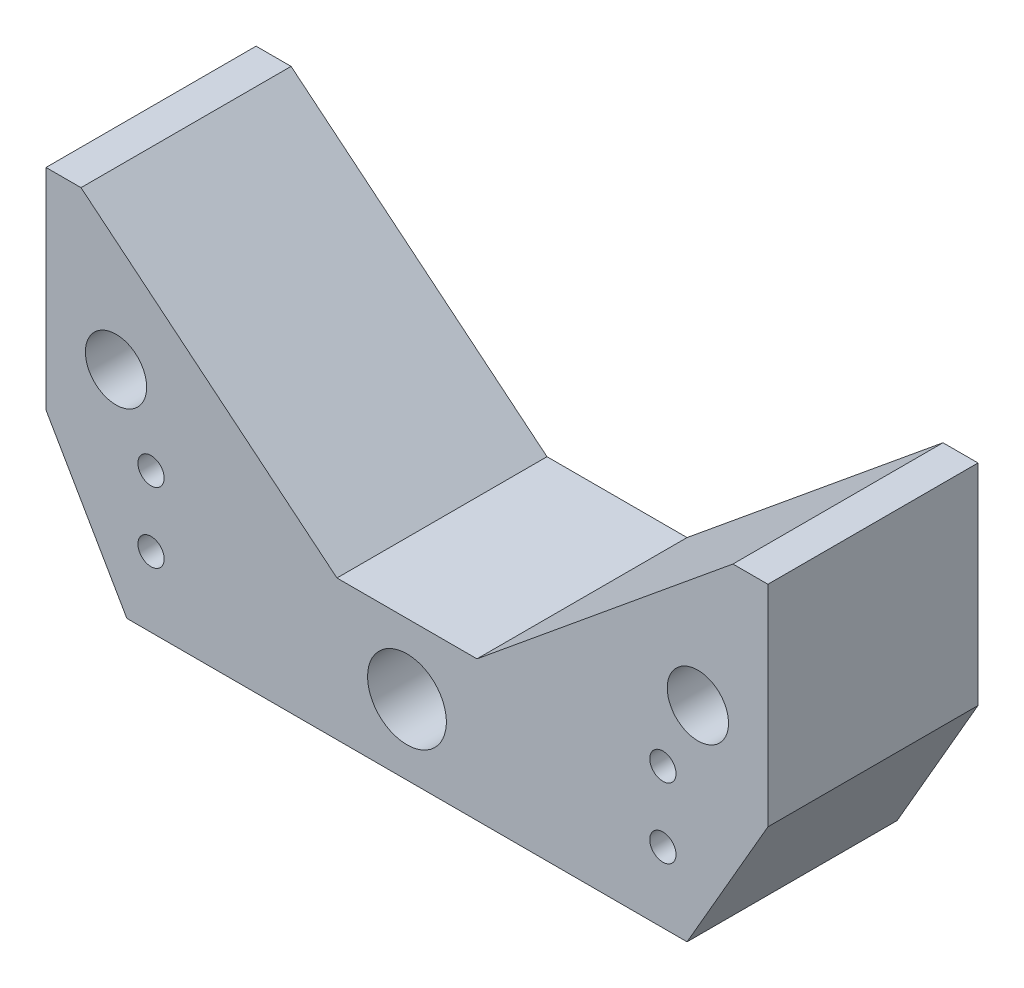
SolidWorks part; units mm, degrees
ref_plane "Front Plane" through (0, 0, 0) normal (0, 0, 1) x (1, 0, 0)
ref_plane "Top Plane" through (0, 0, 0) normal (0, 1, 0) x (1, 0, 0)
ref_plane "Right Plane" through (0, 0, 0) normal (1, 0, 0) x (0, 0, -1)
sketch "Sketch1" plane through (0, 0, 0) normal (0, 0, 1) x (1, 0, 0)
  line L7 (-101.6, 0) -> (101.6, 0)
  line L8 (101.6, 0) -> (130.9294, 50.8)
  line L9 (130.9294, 50.8) -> (130.9294, 127)
  line L10 (130.9294, 127) -> (118.2294, 127)
  line L11 (118.2294, 127) -> (25.4, 50.8)
  line L12 (25.4, 50.8) -> (-25.4, 50.8)
  line L15 (-118.2294, 127) -> (-25.4, 50.8)
  line L16 (-130.9294, 127) -> (-118.2294, 127)
  line L17 (-130.9294, 50.8) -> (-130.9294, 127)
  line L18 (-101.6, 0) -> (-130.9294, 50.8)
  circle A0 centre (105.5294, 76.2) radius 11.1125
  circle A1 centre (92.8294, 50.8) radius 4.7625
  circle A2 centre (92.8294, 25.4) radius 4.7625
  circle A3 centre (0, 25.4) radius 14.2875
  circle A4 centre (-92.8294, 25.4) radius 4.7625
  circle A5 centre (-92.8294, 50.8) radius 4.7625
  circle A6 centre (-105.5294, 76.2) radius 11.1125
  point P0 (0, 0)
  dimension "D7" = 22.225
  dimension "D8" = 25.4
  dimension "D10" = 9.525
  dimension "D11" = 9.525
  dimension "D12" = 12.7
  dimension "D13" = 12.7
  dimension "D14" = 25.4
  dimension "D15" = 25.4
  dimension "D16" = 28.575
  dimension "D2" = 120
  dimension "D3" = 50.8
  dimension "D4" = 76.2
  dimension "D5" = 12.7
  dimension "D9" = 25.4
extrude "Boss-Extrude1" add sketch "Sketch1" along normal blind 76.2 contours A6 | A5 | A4 | A3 | A0 | A1 | A2 | L15 L12 L11 L10 L9 L8 L7 L18 L17 L16
